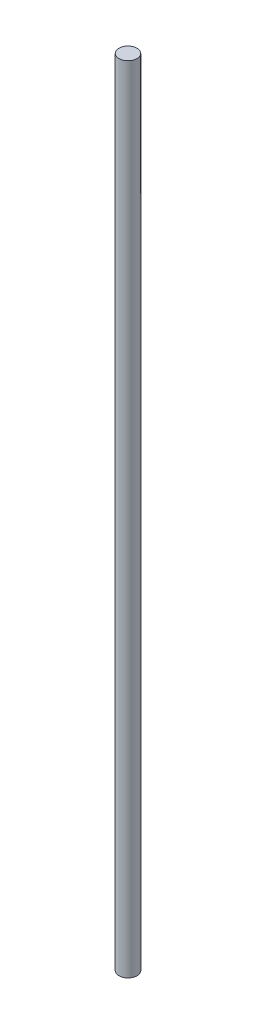
SolidWorks part; units mm, degrees
ref_plane "Alzado" through (0, 0, 0) normal (0, 0, 1) x (1, 0, 0)
ref_plane "Planta" through (0, 0, 0) normal (0, 1, 0) x (1, 0, 0)
ref_plane "Vista lateral" through (0, 0, 0) normal (1, 0, 0) x (0, 0, -1)
sketch "Sketch1" plane through (0, 0, 0) normal (0, 1, 0) x (1, 0, 0)
  circle A0 centre (0, 0) radius 2.5
  dimension "D1" = 5
extrude "Boss-Extrude1" add sketch "Sketch1" along normal blind 220
